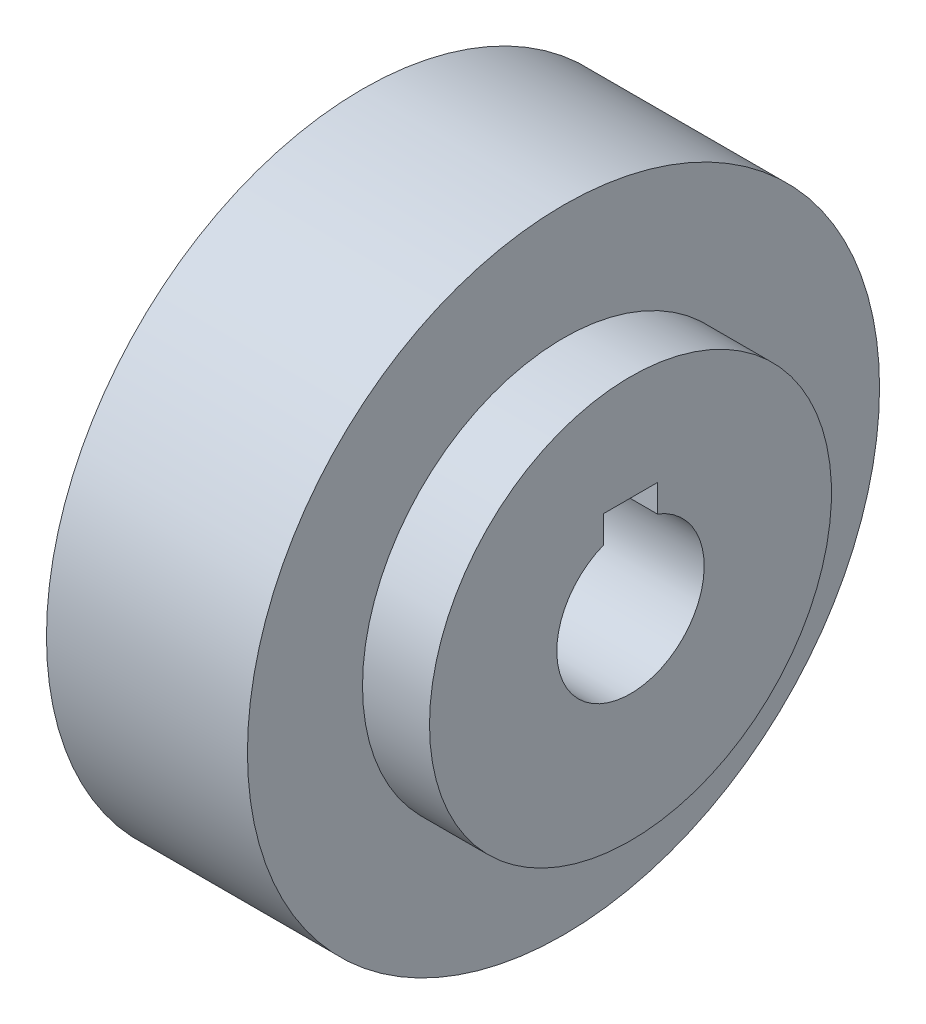
SolidWorks part; units mm, degrees
ref_plane "Front Plane" through (0, 0, 0) normal (0, 0, 1) x (1, 0, 0)
ref_plane "Top Plane" through (0, 0, 0) normal (0, 1, 0) x (1, 0, 0)
ref_plane "Right Plane" through (0, 0, 0) normal (1, 0, 0) x (0, 0, -1)
sketch "Sketch1" plane through (0, 0, 0) normal (0, 0, 1) x (1, 0, 0)
  line L0 (0, 0) -> (67.119, 0) construction
  line L1 (0, 11) -> (0, 47.175)
  line L2 (0, 47.175) -> (30, 47.175)
  line L3 (30, 47.175) -> (30, 30)
  line L4 (30, 30) -> (40, 30)
  line L5 (40, 30) -> (40, 11)
  line L7 (40, 11) -> (0, 11)
  dimension "D1" = 60
  dimension "D2" = 94.35
  dimension "D3" = 30
  dimension "D4" = 22
  dimension "D5" = 40
revolve "Revolve1" add sketch "Sketch1" angle 360 about L0
sketch "Sketch2" plane through (0, 0, 0) normal (-1, 0, 0) x (0, 0, 1)
  line L0 (0, 0) -> (0, 11) construction
  line L1 (-4, 7.7) -> (4, 7.7)
  line L2 (-4, 7.7) -> (-4, 14.3)
  line L3 (-4, 14.3) -> (4, 14.3)
  line L4 (4, 7.7) -> (4, 14.3)
  line L5 (-4, 7.7) -> (4, 14.3) construction
  line L6 (-4, 14.3) -> (4, 7.7) construction
  circle A0 centre (0, 0) radius 11 construction
  point P0 (0, 11)
  dimension "D1" = 8
  dimension "D2" = 3.3
extrude "Cut-Extrude1" cut sketch "Sketch2" against normal through all
